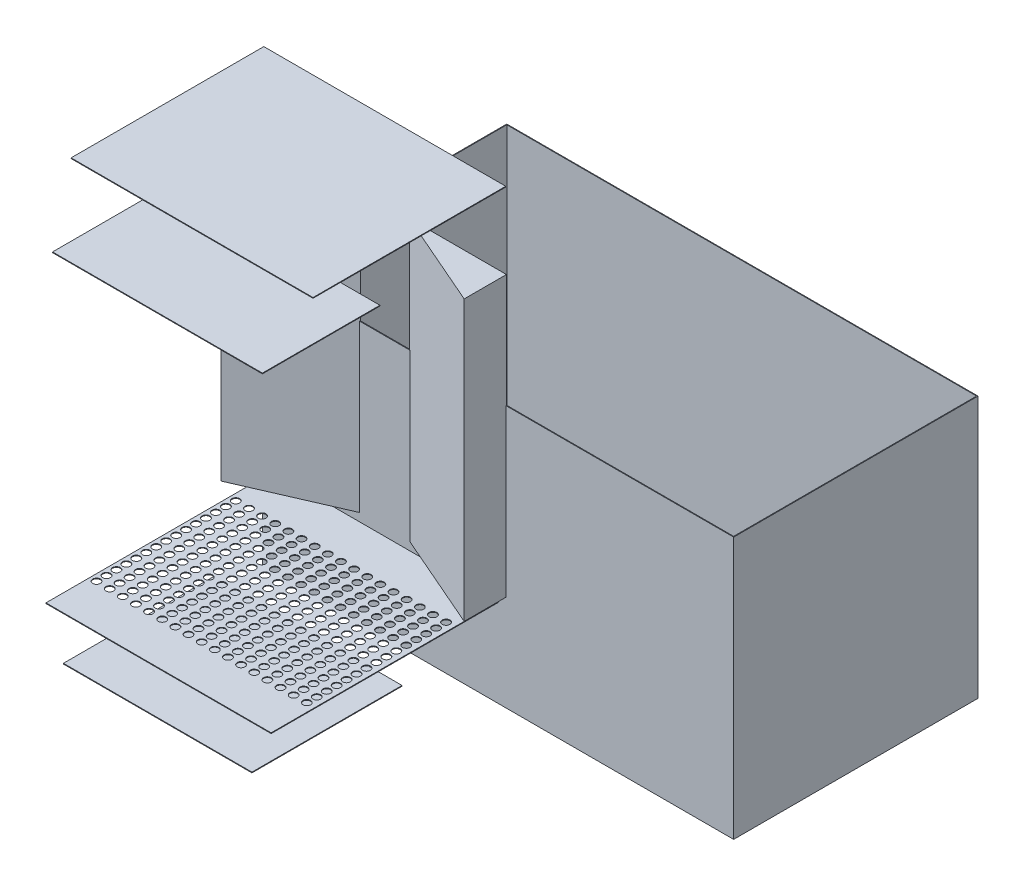
SolidWorks part; units mm, degrees
ref_plane "Спереди" through (0, 0, 0) normal (0, 0, 1) x (1, 0, 0)
ref_plane "Сверху" through (0, 0, 0) normal (0, 1, 0) x (1, 0, 0)
ref_plane "Справа" through (0, 0, 0) normal (1, 0, 0) x (0, 0, -1)
sketch "MASTER_FOOTPRINT" plane through (0, 0, 0) normal (0, 1, 0) x (1, 0, 0)
  line L1 (0, 0) -> (1350, 0)
  line L2 (0, 0) -> (0, 700)
  line L3 (0, 700) -> (1350, 700)
  line L4 (1350, 0) -> (1350, 700)
  dimension "D1" = 1350
  dimension "D2" = 700
extrude "BATH_BASE_PLATE" add sketch "MASTER_FOOTPRINT" along normal blind 750
shell "BATH_SHELL_2MM" thickness 2
sketch "Эскиз1" plane through (0, 0, 0) normal (0, 1, 0) x (1, 0, 0)
  line L1 (80, -220) -> (620, -220)
  line L2 (80, -220) -> (80, -650)
  line L3 (80, -650) -> (620, -650)
  line L4 (620, -220) -> (620, -650)
extrude "INLET_IMPACT_BAFFLE" add sketch "Эскиз1" along normal blind 2 from offset 125 separate body
sketch "Эскиз2" plane through (0, 0, 0) normal (0, 1, 0) x (1, 0, 0)
  line L0 (2, 2) -> (1348, 2) construction
  line L1 (30, 2) -> (675, 2)
  line L2 (30, 2) -> (30, -650)
  line L3 (30, -650) -> (675, -650)
  line L4 (675, 2) -> (675, -650)
  circle A0 centre (48.8235, -125) radius 11
  circle A1 centre (48.8235, -153.5) radius 11
  circle A2 centre (48.8235, -182) radius 11
  circle A3 centre (48.8235, -210.5) radius 11
  circle A4 centre (48.8235, -239) radius 11
  circle A5 centre (48.8235, -267.5) radius 11
  circle A6 centre (48.8235, -296) radius 11
  circle A7 centre (48.8235, -324.5) radius 11
  circle A8 centre (48.8235, -353) radius 11
  circle A9 centre (48.8235, -381.5) radius 11
  circle A10 centre (48.8235, -410) radius 11
  circle A11 centre (48.8235, -438.5) radius 11
  circle A12 centre (48.8235, -467) radius 11
  circle A13 centre (48.8235, -495.5) radius 11
  circle A14 centre (48.8235, -524) radius 11
  circle A15 centre (86.4706, -125) radius 11
  circle A16 centre (86.4706, -153.5) radius 11
  circle A17 centre (86.4706, -182) radius 11
  circle A18 centre (86.4706, -210.5) radius 11
  circle A19 centre (86.4706, -239) radius 11
  circle A20 centre (86.4706, -267.5) radius 11
  circle A21 centre (86.4706, -296) radius 11
  circle A22 centre (86.4706, -324.5) radius 11
  circle A23 centre (86.4706, -353) radius 11
  circle A24 centre (86.4706, -381.5) radius 11
  circle A25 centre (86.4706, -410) radius 11
  circle A26 centre (86.4706, -438.5) radius 11
  circle A27 centre (86.4706, -467) radius 11
  circle A28 centre (86.4706, -495.5) radius 11
  circle A29 centre (86.4706, -524) radius 11
  circle A30 centre (124.1176, -125) radius 11
  circle A31 centre (124.1176, -153.5) radius 11
  circle A32 centre (124.1176, -182) radius 11
  circle A33 centre (124.1176, -210.5) radius 11
  circle A34 centre (124.1176, -239) radius 11
  circle A35 centre (124.1176, -267.5) radius 11
  circle A36 centre (124.1176, -296) radius 11
  circle A37 centre (124.1176, -324.5) radius 11
  circle A38 centre (124.1176, -353) radius 11
  circle A39 centre (124.1176, -381.5) radius 11
  circle A40 centre (124.1176, -410) radius 11
  circle A41 centre (124.1176, -438.5) radius 11
  circle A42 centre (124.1176, -467) radius 11
  circle A43 centre (124.1176, -495.5) radius 11
  circle A44 centre (124.1176, -524) radius 11
  circle A45 centre (161.7647, -125) radius 11
  circle A46 centre (161.7647, -153.5) radius 11
  circle A47 centre (161.7647, -182) radius 11
  circle A48 centre (161.7647, -210.5) radius 11
  circle A49 centre (161.7647, -239) radius 11
  circle A50 centre (161.7647, -267.5) radius 11
  circle A51 centre (161.7647, -296) radius 11
  circle A52 centre (161.7647, -324.5) radius 11
  circle A53 centre (161.7647, -353) radius 11
  circle A54 centre (161.7647, -381.5) radius 11
  circle A55 centre (161.7647, -410) radius 11
  circle A56 centre (161.7647, -438.5) radius 11
  circle A57 centre (161.7647, -467) radius 11
  circle A58 centre (161.7647, -495.5) radius 11
  circle A59 centre (161.7647, -524) radius 11
  circle A60 centre (199.4118, -125) radius 11
  circle A61 centre (199.4118, -153.5) radius 11
  circle A62 centre (199.4118, -182) radius 11
  circle A63 centre (199.4118, -210.5) radius 11
  circle A64 centre (199.4118, -239) radius 11
  circle A65 centre (199.4118, -267.5) radius 11
  circle A66 centre (199.4118, -296) radius 11
  circle A67 centre (199.4118, -324.5) radius 11
  circle A68 centre (199.4118, -353) radius 11
  circle A69 centre (199.4118, -381.5) radius 11
  circle A70 centre (199.4118, -410) radius 11
  circle A71 centre (199.4118, -438.5) radius 11
  circle A72 centre (199.4118, -467) radius 11
  circle A73 centre (199.4118, -495.5) radius 11
  circle A74 centre (199.4118, -524) radius 11
  circle A75 centre (237.0588, -125) radius 11
  circle A76 centre (237.0588, -153.5) radius 11
  circle A77 centre (237.0588, -182) radius 11
  circle A78 centre (237.0588, -210.5) radius 11
  circle A79 centre (237.0588, -239) radius 11
  circle A80 centre (237.0588, -267.5) radius 11
  circle A81 centre (237.0588, -296) radius 11
  circle A82 centre (237.0588, -324.5) radius 11
  circle A83 centre (237.0588, -353) radius 11
  circle A84 centre (237.0588, -381.5) radius 11
  circle A85 centre (237.0588, -410) radius 11
  circle A86 centre (237.0588, -438.5) radius 11
  circle A87 centre (237.0588, -467) radius 11
  circle A88 centre (237.0588, -495.5) radius 11
  circle A89 centre (237.0588, -524) radius 11
  circle A90 centre (274.7059, -125) radius 11
  circle A91 centre (274.7059, -153.5) radius 11
  circle A92 centre (274.7059, -182) radius 11
  circle A93 centre (274.7059, -210.5) radius 11
  circle A94 centre (274.7059, -239) radius 11
  circle A95 centre (274.7059, -267.5) radius 11
  circle A96 centre (274.7059, -296) radius 11
  circle A97 centre (274.7059, -324.5) radius 11
  circle A98 centre (274.7059, -353) radius 11
  circle A99 centre (274.7059, -381.5) radius 11
  circle A100 centre (274.7059, -410) radius 11
  circle A101 centre (274.7059, -438.5) radius 11
  circle A102 centre (274.7059, -467) radius 11
  circle A103 centre (274.7059, -495.5) radius 11
  circle A104 centre (274.7059, -524) radius 11
  circle A105 centre (312.3529, -125) radius 11
  circle A106 centre (312.3529, -153.5) radius 11
  circle A107 centre (312.3529, -182) radius 11
  circle A108 centre (312.3529, -210.5) radius 11
  circle A109 centre (312.3529, -239) radius 11
  circle A110 centre (312.3529, -267.5) radius 11
  circle A111 centre (312.3529, -296) radius 11
  circle A112 centre (312.3529, -324.5) radius 11
  circle A113 centre (312.3529, -353) radius 11
  circle A114 centre (312.3529, -381.5) radius 11
  circle A115 centre (312.3529, -410) radius 11
  circle A116 centre (312.3529, -438.5) radius 11
  circle A117 centre (312.3529, -467) radius 11
  circle A118 centre (312.3529, -495.5) radius 11
  circle A119 centre (312.3529, -524) radius 11
  circle A120 centre (350, -125) radius 11
  circle A121 centre (350, -153.5) radius 11
  circle A122 centre (350, -182) radius 11
  circle A123 centre (350, -210.5) radius 11
  circle A124 centre (350, -239) radius 11
  circle A125 centre (350, -267.5) radius 11
  circle A126 centre (350, -296) radius 11
  circle A127 centre (350, -324.5) radius 11
  circle A128 centre (350, -353) radius 11
  circle A129 centre (350, -381.5) radius 11
  circle A130 centre (350, -410) radius 11
  circle A131 centre (350, -438.5) radius 11
  circle A132 centre (350, -467) radius 11
  circle A133 centre (350, -495.5) radius 11
  circle A134 centre (350, -524) radius 11
  circle A135 centre (387.6471, -125) radius 11
  circle A136 centre (387.6471, -153.5) radius 11
  circle A137 centre (387.6471, -182) radius 11
  circle A138 centre (387.6471, -210.5) radius 11
  circle A139 centre (387.6471, -239) radius 11
  circle A140 centre (387.6471, -267.5) radius 11
  circle A141 centre (387.6471, -296) radius 11
  circle A142 centre (387.6471, -324.5) radius 11
  circle A143 centre (387.6471, -353) radius 11
  circle A144 centre (387.6471, -381.5) radius 11
  circle A145 centre (387.6471, -410) radius 11
  circle A146 centre (387.6471, -438.5) radius 11
  circle A147 centre (387.6471, -467) radius 11
  circle A148 centre (387.6471, -495.5) radius 11
  circle A149 centre (387.6471, -524) radius 11
  circle A150 centre (425.2941, -125) radius 11
  circle A151 centre (425.2941, -153.5) radius 11
  circle A152 centre (425.2941, -182) radius 11
  circle A153 centre (425.2941, -210.5) radius 11
  circle A154 centre (425.2941, -239) radius 11
  circle A155 centre (425.2941, -267.5) radius 11
  circle A156 centre (425.2941, -296) radius 11
  circle A157 centre (425.2941, -324.5) radius 11
  circle A158 centre (425.2941, -353) radius 11
  circle A159 centre (425.2941, -381.5) radius 11
  circle A160 centre (425.2941, -410) radius 11
  circle A161 centre (425.2941, -438.5) radius 11
  circle A162 centre (425.2941, -467) radius 11
  circle A163 centre (425.2941, -495.5) radius 11
  circle A164 centre (425.2941, -524) radius 11
  circle A165 centre (462.9412, -125) radius 11
  circle A166 centre (462.9412, -153.5) radius 11
  circle A167 centre (462.9412, -182) radius 11
  circle A168 centre (462.9412, -210.5) radius 11
  circle A169 centre (462.9412, -239) radius 11
  circle A170 centre (462.9412, -267.5) radius 11
  circle A171 centre (462.9412, -296) radius 11
  circle A172 centre (462.9412, -324.5) radius 11
  circle A173 centre (462.9412, -353) radius 11
  circle A174 centre (462.9412, -381.5) radius 11
  circle A175 centre (462.9412, -410) radius 11
  circle A176 centre (462.9412, -438.5) radius 11
  circle A177 centre (462.9412, -467) radius 11
  circle A178 centre (462.9412, -495.5) radius 11
  circle A179 centre (462.9412, -524) radius 11
  circle A180 centre (500.5882, -125) radius 11
  circle A181 centre (500.5882, -153.5) radius 11
  circle A182 centre (500.5882, -182) radius 11
  circle A183 centre (500.5882, -210.5) radius 11
  circle A184 centre (500.5882, -239) radius 11
  circle A185 centre (500.5882, -267.5) radius 11
  circle A186 centre (500.5882, -296) radius 11
  circle A187 centre (500.5882, -324.5) radius 11
  circle A188 centre (500.5882, -353) radius 11
  circle A189 centre (500.5882, -381.5) radius 11
  circle A190 centre (500.5882, -410) radius 11
  circle A191 centre (500.5882, -438.5) radius 11
  circle A192 centre (500.5882, -467) radius 11
  circle A193 centre (500.5882, -495.5) radius 11
  circle A194 centre (500.5882, -524) radius 11
  circle A195 centre (538.2353, -125) radius 11
  circle A196 centre (538.2353, -153.5) radius 11
  circle A197 centre (538.2353, -182) radius 11
  circle A198 centre (538.2353, -210.5) radius 11
  circle A199 centre (538.2353, -239) radius 11
  circle A200 centre (538.2353, -267.5) radius 11
  circle A201 centre (538.2353, -296) radius 11
  circle A202 centre (538.2353, -324.5) radius 11
  circle A203 centre (538.2353, -353) radius 11
  circle A204 centre (538.2353, -381.5) radius 11
  circle A205 centre (538.2353, -410) radius 11
  circle A206 centre (538.2353, -438.5) radius 11
  circle A207 centre (538.2353, -467) radius 11
  circle A208 centre (538.2353, -495.5) radius 11
  circle A209 centre (538.2353, -524) radius 11
  circle A210 centre (575.8824, -125) radius 11
  circle A211 centre (575.8824, -153.5) radius 11
  circle A212 centre (575.8824, -182) radius 11
  circle A213 centre (575.8824, -210.5) radius 11
  circle A214 centre (575.8824, -239) radius 11
  circle A215 centre (575.8824, -267.5) radius 11
  circle A216 centre (575.8824, -296) radius 11
  circle A217 centre (575.8824, -324.5) radius 11
  circle A218 centre (575.8824, -353) radius 11
  circle A219 centre (575.8824, -381.5) radius 11
  circle A220 centre (575.8824, -410) radius 11
  circle A221 centre (575.8824, -438.5) radius 11
  circle A222 centre (575.8824, -467) radius 11
  circle A223 centre (575.8824, -495.5) radius 11
  circle A224 centre (575.8824, -524) radius 11
  circle A225 centre (613.5294, -125) radius 11
  circle A226 centre (613.5294, -153.5) radius 11
  circle A227 centre (613.5294, -182) radius 11
  circle A228 centre (613.5294, -210.5) radius 11
  circle A229 centre (613.5294, -239) radius 11
  circle A230 centre (613.5294, -267.5) radius 11
  circle A231 centre (613.5294, -296) radius 11
  circle A232 centre (613.5294, -324.5) radius 11
  circle A233 centre (613.5294, -353) radius 11
  circle A234 centre (613.5294, -381.5) radius 11
  circle A235 centre (613.5294, -410) radius 11
  circle A236 centre (613.5294, -438.5) radius 11
  circle A237 centre (613.5294, -467) radius 11
  circle A238 centre (613.5294, -495.5) radius 11
  circle A239 centre (613.5294, -524) radius 11
  circle A240 centre (651.1765, -125) radius 11
  circle A241 centre (651.1765, -153.5) radius 11
  circle A242 centre (651.1765, -182) radius 11
  circle A243 centre (651.1765, -210.5) radius 11
  circle A244 centre (651.1765, -239) radius 11
  circle A245 centre (651.1765, -267.5) radius 11
  circle A246 centre (651.1765, -296) radius 11
  circle A247 centre (651.1765, -324.5) radius 11
  circle A248 centre (651.1765, -353) radius 11
  circle A249 centre (651.1765, -381.5) radius 11
  circle A250 centre (651.1765, -410) radius 11
  circle A251 centre (651.1765, -438.5) radius 11
  circle A252 centre (651.1765, -467) radius 11
  circle A253 centre (651.1765, -495.5) radius 11
  circle A254 centre (651.1765, -524) radius 11
extrude "DISTRIBUTOR_D22" add sketch "Эскиз2" along normal blind 2 from offset 250 separate body
sketch "Эскиз3" plane through (0, 0, 0) normal (0, 1, 0) x (1, 0, 0)
  line L0 (30, -650) -> (675, -650) construction
  line L1 (48.8235, -313.5) -> (650, -313.5)
  line L2 (48.8235, -313.5) -> (48.8235, -650)
  line L3 (48.8235, -650) -> (650, -650)
  line L4 (650, -313.5) -> (650, -650)
  circle A0 centre (48.8235, -324.5) radius 11 construction
extrude "OUTLET_SUBMERGED_BAFFLE" add sketch "Эскиз3" along normal blind 2 from offset 1130 separate body
sketch "Эскиз4" plane through (0, 0, 0) normal (0, 1, 0) x (1, 0, 0)
  line L1 (2, 2) -> (695, 2)
  line L2 (2, 2) -> (2, -550)
  line L3 (2, -550) -> (695, -550)
  line L4 (695, 2) -> (695, -550)
extrude "OVERFLOW_WEIR_Z550" add sketch "Эскиз4" along normal blind 2 from offset 1290 separate body
sketch "Эскиз5" plane through (0, 0, 0) normal (0, 1, 0) x (1, 0, 0)
  line L0 (2, 1) -> (2, -120)
  line L1 (2, -120) -> (280, 1)
  line L2 (280, 1) -> (2, 1)
  line L3 (698, 1) -> (698, -120)
  line L4 (698, -120) -> (420, 1)
  line L5 (420, 1) -> (698, 1)
extrude "SLOPED_SEDIMENT_FLOOR" add sketch "Эскиз5" along normal blind 800 from offset 275
sketch3d "SCREW_AXIS_30DEG_REFERENCE"
  line L0 (350, 400, 70) -> (350, 1450, 676.2178)
equation "\"AI_Q_Peak\"= 0.006"
equation "\"AI_B_Bath\"= 700"
equation "\"AI_L_Settle\"= 900"
equation "\"AI_L_Inlet\"= 250"
equation "\"AI_L_Outlet\"= 200"
equation "\"AI_L_Bath\"= 1350"
equation "\"AI_H_Water\"= 550"
equation "\"AI_H_Freeboard\"= 200"
equation "\"AI_H_Bath\"= 750"
equation "\"AI_Shell_Thickness\"= 2"
equation "\"AI_Inlet_DN\"= 100"
equation "\"AI_Weir_Width\"= 600"
equation "\"AI_Inlet_Baffle_Offset\"= 125"
equation "\"AI_Distributor_Open_Area\"= 0.28"
equation "\"AI_Distributor_Hole_Dia\"= 22"
equation "\"AI_Distributor_Blind_Zone\"= 110"
equation "\"AI_Outlet_Baffle_Depth\"= 250"
equation "\"AI_Screw_Diameter\"= 100"
equation "\"AI_Screw_Pitch\"= 100"
equation "\"AI_Screw_Angle\"= 30"
equation "\"AI_Screw_Rpm\"= 15"
equation "\"AI_Screw_Clearance\"= 5"
equation "\"AI_Liner_Thickness\"= 5"
equation "\"AI_Discharge_Height\"= 650"
equation "\"AI_Frame_Height\"= 500"
equation "\"D1@MASTER_FOOTPRINT\" = \"AI_L_Bath\""
equation "\"D2@MASTER_FOOTPRINT\" = \"AI_B_Bath\""
equation "\"D1@BATH_BASE_PLATE\" = \"AI_H_Bath\""
